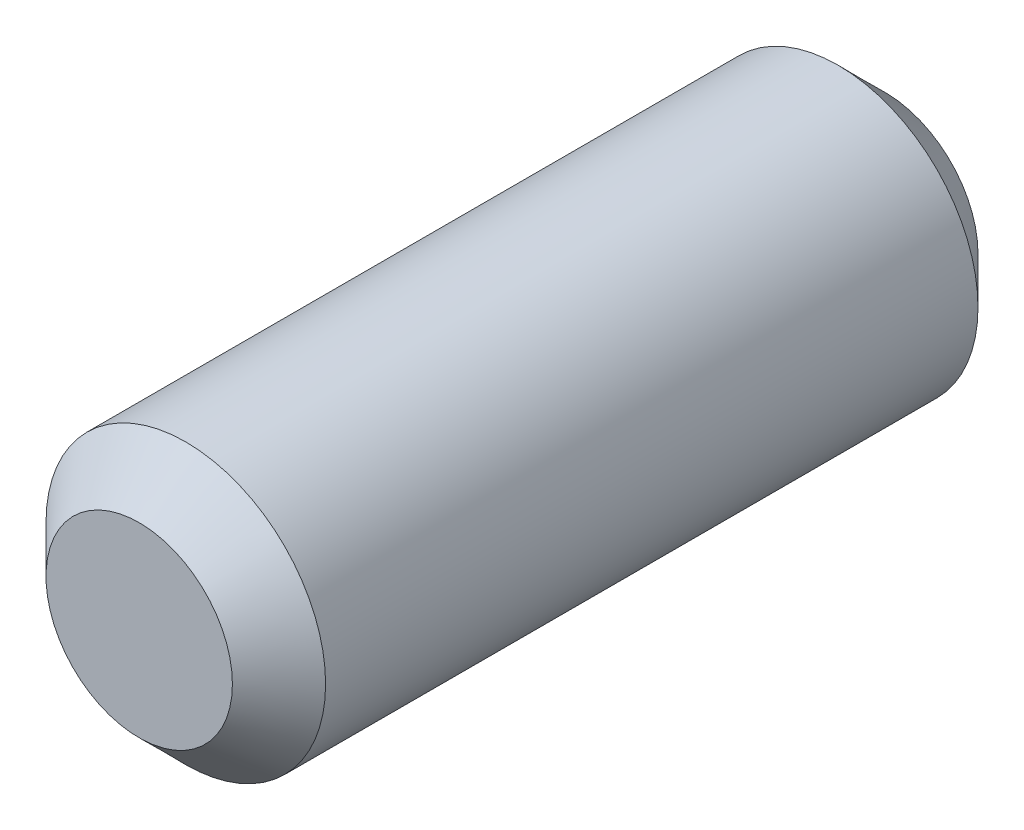
SolidWorks part; units mm, degrees
ref_plane "Front" through (0, 0, 0) normal (0, 0, 1) x (1, 0, 0)
ref_plane "Top" through (0, 0, 0) normal (0, 1, 0) x (1, 0, 0)
ref_plane "Right" through (0, 0, 0) normal (1, 0, 0) x (0, 0, -1)
other "Configuration Table"
sketch "Esquisse1" plane through (0, 0, 0) normal (0, 0, 1) x (1, 0, 0)
  circle A0 centre (0, 0) radius 1.5
  point P2 (0, 0.0231)
  point P3 (0, 0)
  dimension "D1" = 3
extrude "Boss.-Extru.1" add sketch "Esquisse1" along normal blind 8
chamfer "Chanfrein1" distance 0.5 angle 45 2 edges at (1.5, 0, 0) (1.5, 0, 8)
